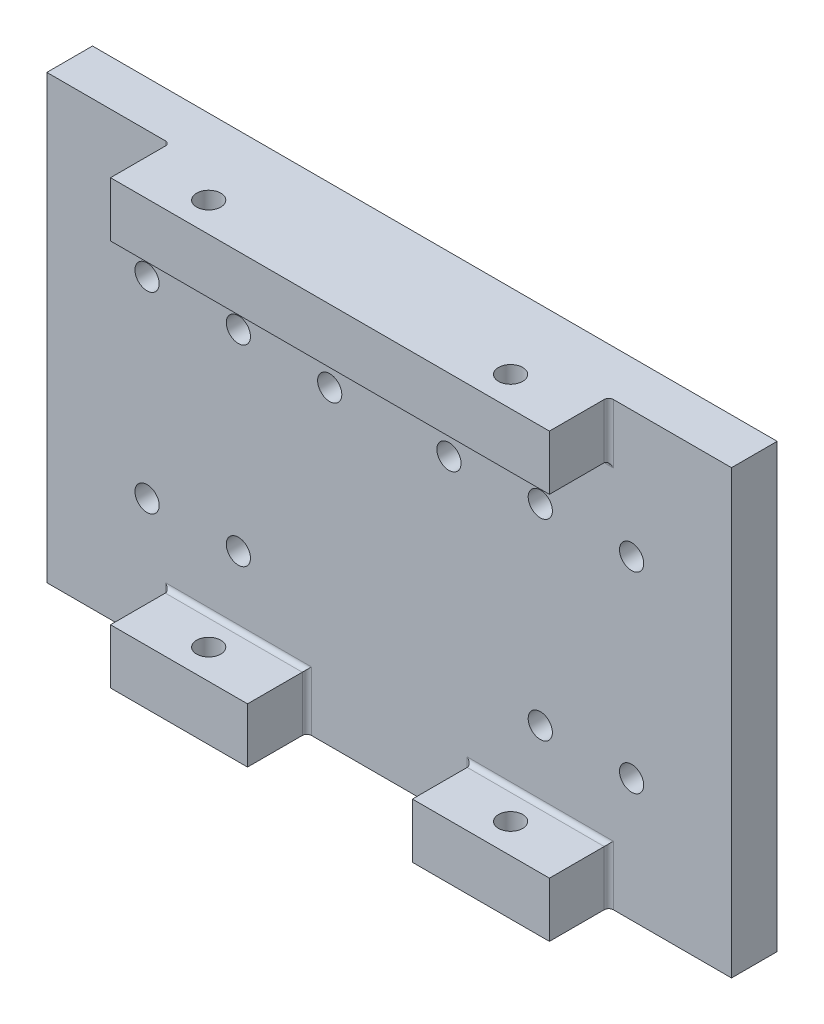
SolidWorks part; units mm, degrees
ref_plane "Front Plane" through (0, 0, 0) normal (0, 0, 1) x (1, 0, 0)
ref_plane "Top Plane" through (0, 0, 0) normal (0, 1, 0) x (1, 0, 0)
ref_plane "Right Plane" through (0, 0, 0) normal (1, 0, 0) x (0, 0, -1)
sketch "Sketch3" plane through (0, 0, 0) normal (0, 0, 1) x (1, 0, 0)
  line L52 (-75.0004, 52.83) -> (74.9996, 52.83)
  line L54 (74.9996, 52.83) -> (-75.0004, 52.83)
  line L57 (-75.0004, 52.83) -> (74.9287, 52.83)
  line L58 (-75.0004, 52.83) -> (-75.0004, -43.95)
  line L59 (-75.0004, -43.95) -> (74.9287, -43.95)
  line L60 (74.9287, 52.83) -> (74.9287, -43.95)
  circle A20 centre (-53.0554, -17.005) radius 2.65
  circle A32 centre (-33.055, -17.005) radius 2.65
  circle A35 centre (33.055, -17.005) radius 2.65
  circle A36 centre (53.0546, -17.005) radius 2.65
  circle A38 centre (-13.055, 24.0274) radius 2.65
  circle A39 centre (13.055, 24.0274) radius 2.65
  circle A43 centre (-53.0554, 25.0274) radius 2.65
  circle A44 centre (-33.055, 25.0274) radius 2.65
  circle A47 centre (33.055, 25.0274) radius 2.65
  circle A48 centre (53.0546, 25.0274) radius 2.65
  point P0 (0, 0)
  dimension "D3" = 5.3
  dimension "D4" = 96.78
  dimension "D6" = 5.3
  dimension "D8" = 5.3
  dimension "D13" = 5.3
  dimension "D9" = 5.3
  dimension "D18" = 5.3
  dimension "D5" = 5.3
  dimension "D22" = 5.3
  dimension "D24" = 5.3
  dimension "D25" = 5.3
extrude "Boss-Extrude1" add sketch "Sketch3" along normal blind 10
sketch "Sketch4" plane through (0, 0, 10) normal (0, 0, 1) x (1, 0, 0)
  line L0 (-75.0004, -43.95) -> (74.9287, -43.95) construction
  line L1 (-75.0004, 52.83) -> (74.9287, 52.83) construction
  line L2 (-33.055, 40.83) -> (-48.055, 40.83)
  line L3 (-48.055, -43.95) -> (-18.055, -43.95)
  line L4 (-48.055, -43.95) -> (-48.055, -31.95)
  line L5 (-48.055, 40.83) -> (-18.055, 40.83)
  line L6 (-48.055, 40.83) -> (-48.055, 52.83)
  line L7 (-48.055, 52.83) -> (-18.055, 52.83)
  line L9 (-48.055, -31.95) -> (-18.055, -31.95)
  line L10 (18.055, 40.83) -> (48.055, 40.83)
  line L12 (18.055, 52.83) -> (48.055, 52.83)
  line L13 (48.055, 40.83) -> (48.055, 52.83)
  line L14 (-18.055, -43.95) -> (-18.055, -31.95)
  line L15 (-18.055, 40.83) -> (18.055, 40.83)
  line L16 (18.055, -43.95) -> (48.055, -43.95)
  line L17 (18.055, -43.95) -> (18.055, -31.95)
  line L18 (18.055, -31.95) -> (48.055, -31.95)
  line L19 (48.055, -43.95) -> (48.055, -31.95)
  line L20 (-18.055, 52.83) -> (18.055, 52.83)
  dimension "D1" = 30
  dimension "D2" = 12
  dimension "D3" = 12
  dimension "D4" = 12
  dimension "D5" = 30
  dimension "D6" = 12
extrude "Boss-Extrude4" add sketch "Sketch4" along normal blind 13
sketch "Sketch5" plane through (0, -31.95, 0) normal (0, 1, 0) x (1, 0, 0)
  circle A0 centre (33.055, -16.5) radius 2.65
  circle A1 centre (-33.055, -16.5) radius 2.65
  dimension "D3" = 5.3
  dimension "D2" = 5.3
extrude "Cut-Extrude1" cut sketch "Sketch5" against normal through all both and the other way through all
fillet "Fillet1" radius 1 9 edges at (48.055, -37.95, 10) (33.055, -31.95, 10) (18.055, -37.95, 10) (-18.055, -37.95, 10) (-33.055, -31.95, 10) (-48.055, -37.95, 10) (48.055, 46.83, 10) (0, 40.83, 10) (-48.055, 46.83, 10)
